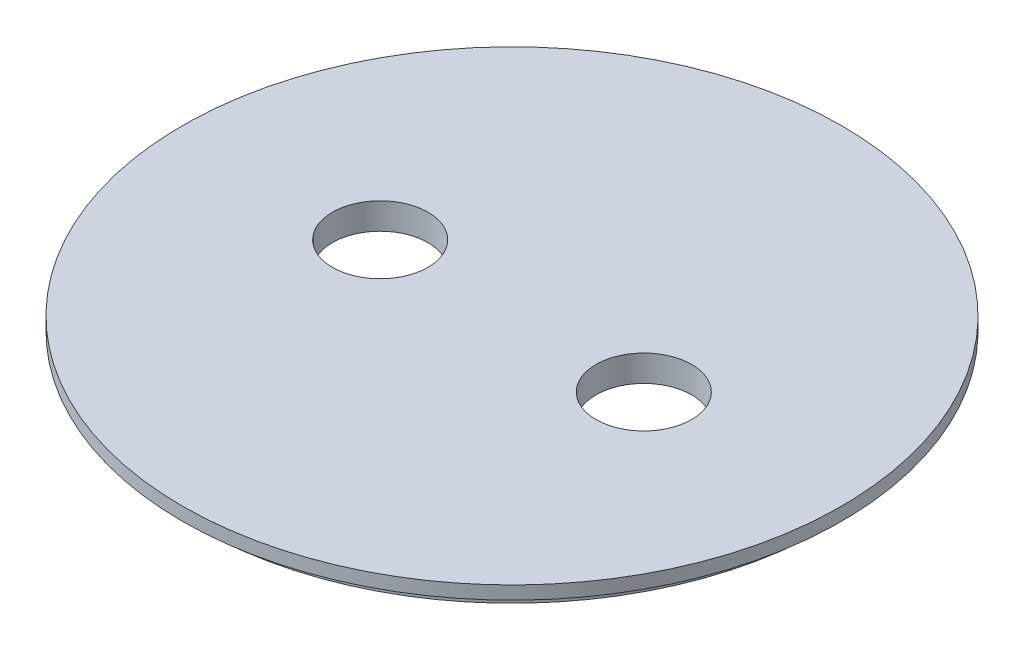
SolidWorks part; units mm, degrees
ref_plane "Front Plane" through (0, 0, 0) normal (0, 0, 1) x (1, 0, 0)
ref_plane "Top Plane" through (0, 0, 0) normal (0, 1, 0) x (1, 0, 0)
ref_plane "Right Plane" through (0, 0, 0) normal (1, 0, 0) x (0, 0, -1)
sketch "Sketch1" plane through (0, 0, 0) normal (0, 1, 0) x (1, 0, 0)
  circle A0 centre (0, 0) radius 50
  dimension "D1" = 100
extrude "Boss-Extrude1" add sketch "Sketch1" along normal blind 2
sketch "Sketch2" plane through (0, 0, 0) normal (0, -1, 0) x (1, 0, 0)
  circle A0 centre (0, 0) radius 47.75
  dimension "D1" = 95.5
extrude "Boss-Extrude2" add sketch "Sketch2" along normal blind 2
sketch "Sketch3" plane through (0, 2, 0) normal (0, 1, 0) x (1, 0, 0)
  line L1 (-20, 15) -> (20, 15)
  line L2 (-20, 15) -> (-20, -15)
  line L3 (-20, -15) -> (20, -15)
  line L4 (20, 15) -> (20, -15)
  line L5 (-20, 15) -> (20, -15) construction
  line L6 (-20, -15) -> (20, 15) construction
  circle A0 centre (-20, 0) radius 7.25
  circle A1 centre (20, 0) radius 7.25
  point P0 (0, 0)
  dimension "D3" = 14.5
  dimension "D4" = 14.5
  dimension "D1" = 40
  dimension "D2" = 30
extrude "Cut-Extrude1" cut sketch "Sketch3" against normal through all contours A1 | A0
